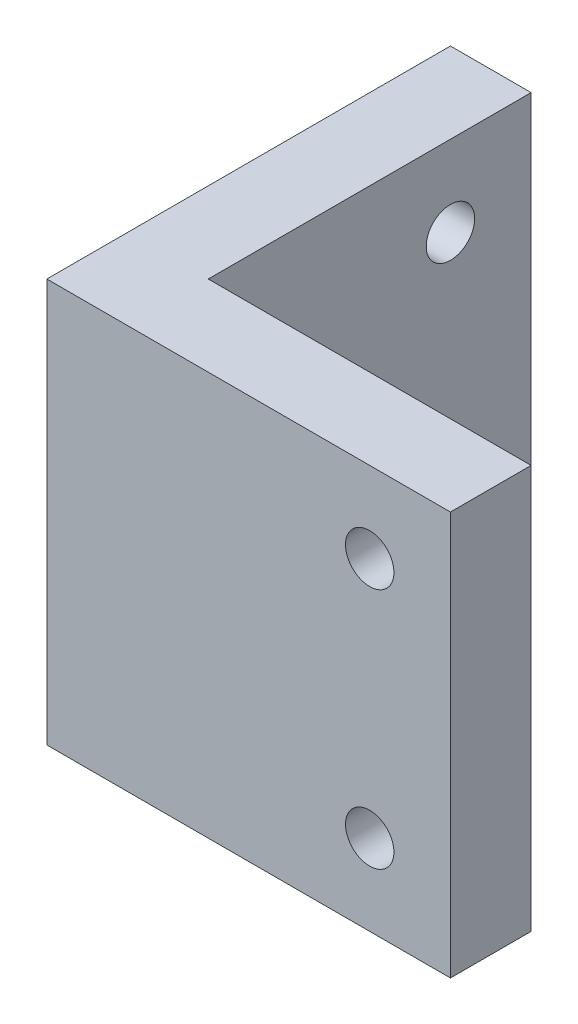
SolidWorks part; units mm, degrees
ref_plane "前视基准面" through (0, 0, 0) normal (0, 0, 1) x (1, 0, 0)
ref_plane "上视基准面" through (0, 0, 0) normal (0, 1, 0) x (1, 0, 0)
ref_plane "右视基准面" through (0, 0, 0) normal (1, 0, 0) x (0, 0, -1)
sketch "草图1" plane through (0, 0, 0) normal (0, 1, 0) x (1, 0, 0)
  line L0 (0, 0) -> (25, 0)
  line L1 (25, 0) -> (25, 5)
  line L2 (25, 5) -> (5, 5)
  line L3 (5, 5) -> (5, 25)
  line L4 (5, 25) -> (0, 25)
  line L5 (0, 25) -> (0, 0)
  dimension "D1" = 25
  dimension "D2" = 25
  dimension "D3" = 5
  dimension "D4" = 5
extrude "凸台-拉伸1" add sketch "草图1" along normal blind 25 contours L3 L4 L5 L0 L1 L2
sketch "草图2" plane through (0, 0, -5) normal (0, 0, -1) x (-1, 0, 0)
  line L0 (-20, 20) -> (-20, 5) construction
  line L1 (-5, 25) -> (-5, 0) construction
  line L3 (-25, 25) -> (-5, 25) construction
  circle A0 centre (-20, 20) radius 1.5
  circle A1 centre (-20, 5) radius 1.5
  dimension "D1" = 3
  dimension "D2" = 3
  dimension "D3" = 15
  dimension "D4" = 15
  dimension "D5" = 5
extrude "切除-拉伸1" cut sketch "草图2" against normal blind 10
sketch "草图3" plane through (5, 0, 0) normal (1, 0, 0) x (0, 0, -1)
  line L0 (20, 20) -> (20, 5) construction
  line L1 (5, 25) -> (5, 0) construction
  line L2 (5, 25) -> (25, 25) construction
  circle A0 centre (20, 20) radius 1.5
  circle A1 centre (20, 5.0703) radius 1.5
  dimension "D1" = 3
  dimension "D2" = 3
  dimension "D3" = 15
  dimension "D4" = 15
  dimension "D5" = 5
extrude "切除-拉伸2" cut sketch "草图3" against normal blind 10
